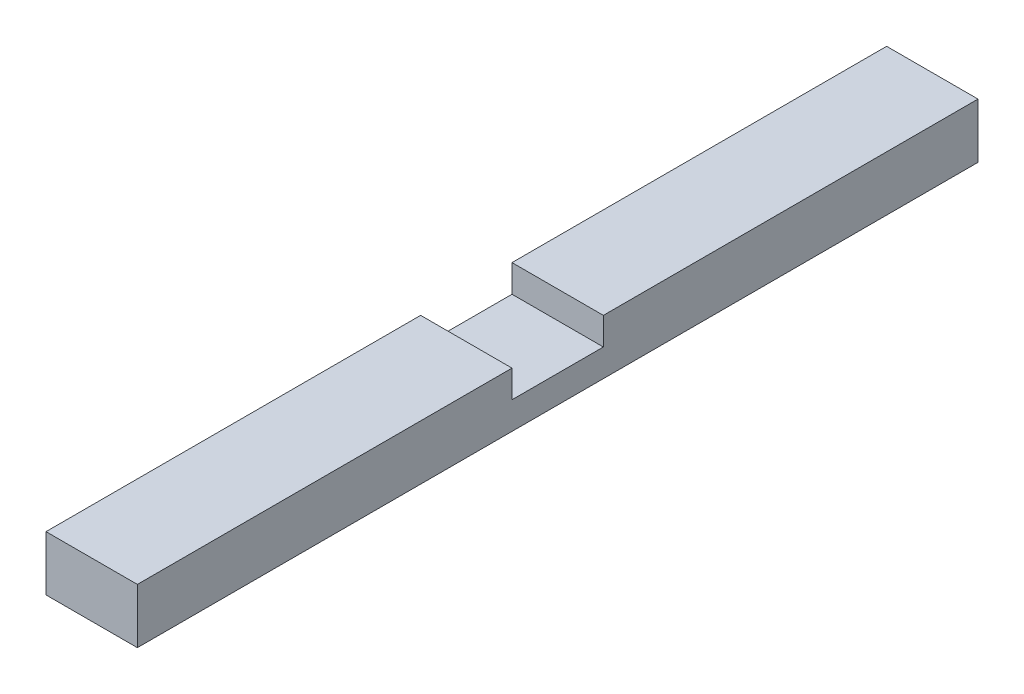
SolidWorks part; units mm, degrees
material "Kiefer"
ref_plane "Ebene vorne" through (0, 0, 0) normal (0, 0, 1) x (1, 0, 0)
ref_plane "Ebene oben" through (0, 0, 0) normal (0, 1, 0) x (1, 0, 0)
ref_plane "Ebene rechts" through (0, 0, 0) normal (1, 0, 0) x (0, 0, -1)
sketch "Skizze1" plane through (0, 0, 0) normal (0, 0, 1) x (1, 0, 0)
  line L0 (0, 0) -> (0, 40.512) construction
  line L2 (50, 30) -> (-50, 30)
  line L3 (50, 30) -> (50, -30)
  line L4 (50, -30) -> (-50, -30)
  line L5 (-50, 30) -> (-50, -30)
  line L6 (50, 30) -> (-50, -30) construction
  line L7 (50, -30) -> (-50, 30) construction
  dimension "D1" = 100
  dimension "D2" = 60
extrude "Aufsatz-Linear austragen1" add sketch "Skizze1" along normal mid plane 920
sketch "Skizze2" plane through (0, 30, 0) normal (0, 1, 0) x (1, 0, 0)
  line L0 (50, -460) -> (50, 460) construction
  line L1 (-50, -50) -> (50, -50)
  line L2 (-50, -50) -> (-50, 50)
  line L3 (-50, 50) -> (50, 50)
  line L4 (50, -50) -> (50, 50)
  line L5 (-50, -50) -> (50, 50) construction
  line L6 (-50, 50) -> (50, -50) construction
  point P0 (0, 0)
  dimension "D1" = 100
extrude "Schnitt-Linear austragen1" cut sketch "Skizze2" against normal blind 30
